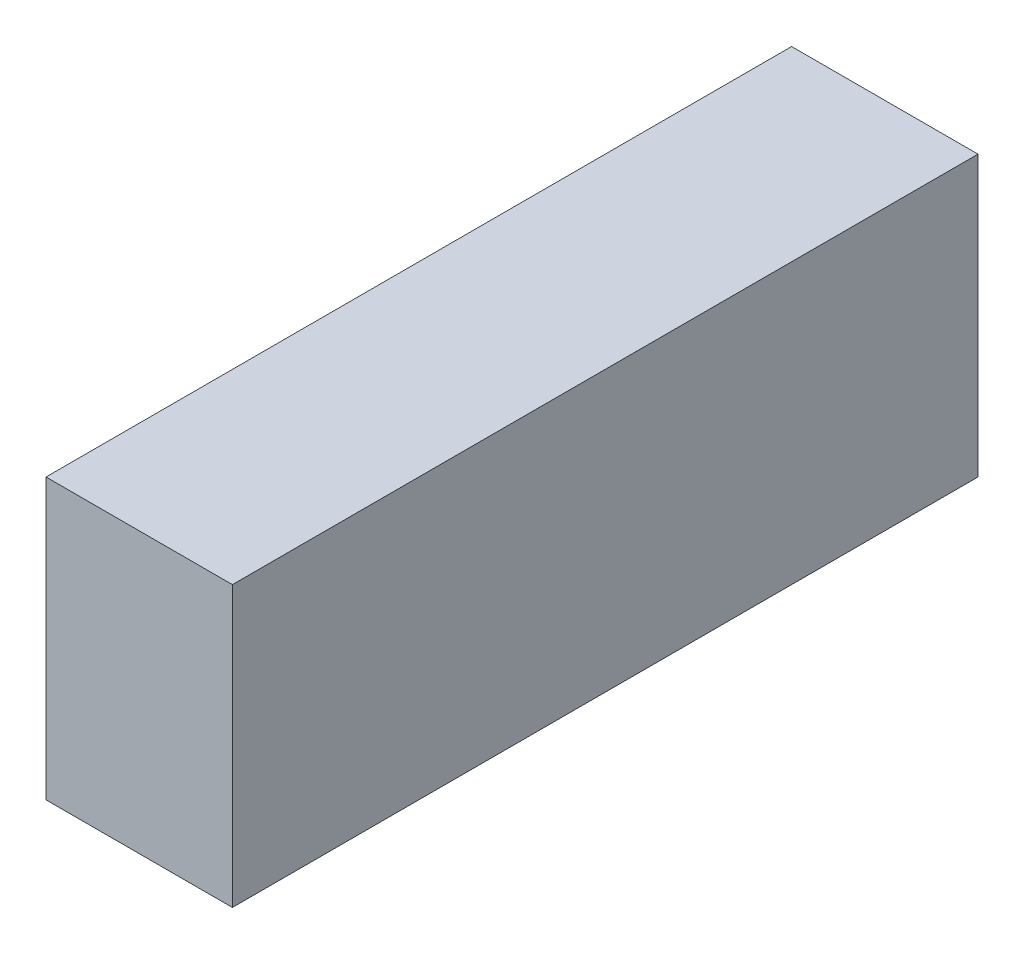
SolidWorks part; units mm, degrees
ref_plane "Front Plane" through (0, 0, 0) normal (0, 0, 1) x (1, 0, 0)
ref_plane "Top Plane" through (0, 0, 0) normal (0, 1, 0) x (1, 0, 0)
ref_plane "Right Plane" through (0, 0, 0) normal (1, 0, 0) x (0, 0, -1)
other "Configuration Table"
sketch "Sketch1" plane through (0, 0, 0) normal (0, 0, 1) x (1, 0, 0)
  line L1 (2, 33) -> (12, 33)
  line L2 (2, 33) -> (2, 48)
  line L3 (2, 48) -> (12, 48)
  line L4 (12, 33) -> (12, 48)
extrude "CEK_donmus_kayis_baglanti_pabucu_1" add sketch "Sketch1" against normal blind 40 from offset 40 separate body
